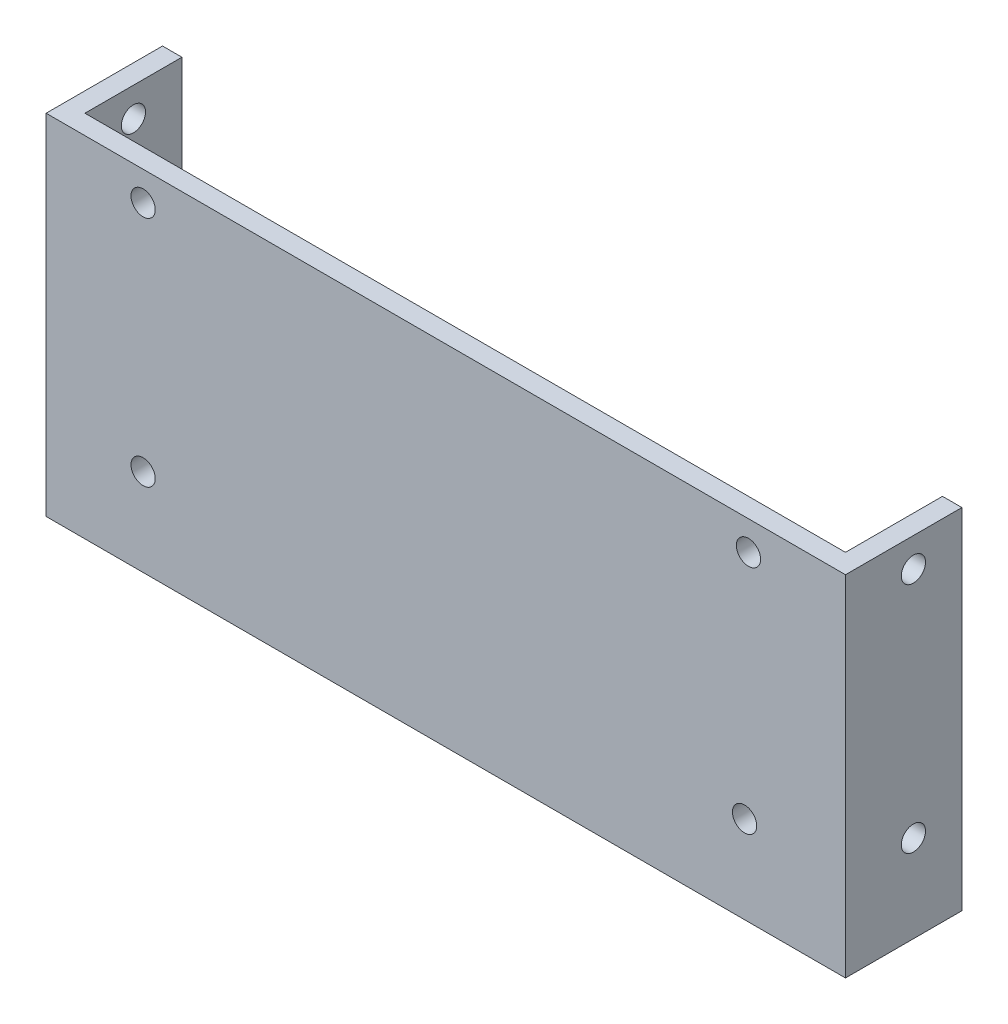
SolidWorks part; units mm, degrees
ref_plane "前视基准面" through (0, 0, 0) normal (0, 0, 1) x (1, 0, 0)
ref_plane "上视基准面" through (0, 0, 0) normal (0, 1, 0) x (1, 0, 0)
ref_plane "右视基准面" through (0, 0, 0) normal (1, 0, 0) x (0, 0, -1)
other "Configuration Table"
sketch "草图1" plane through (0, 0, 0) normal (0, 0, 1) x (1, 0, 0)
  line L1 (0, 0) -> (82.4, 0)
  line L2 (0, 0) -> (0, 6)
  line L3 (0, 6) -> (82.4, 6)
  line L4 (82.4, 0) -> (82.4, 6)
  dimension "D1" = 6
  dimension "D2" = 82.4
extrude "凸台-拉伸1" add sketch "草图1" along normal blind 2
sketch "草图2" plane through (0, 0, 0) normal (0, 0, -1) x (-1, 0, 0)
  line L0 (0, 6) -> (-2, 6)
  line L1 (-82.4, 6) -> (0, 6) construction
  line L2 (-2, 6) -> (-2, 0)
  line L3 (0, 0) -> (-82.4, 0) construction
  line L4 (-2, 0) -> (0, 0)
  line L5 (0, 0) -> (0, 6)
  line L6 (-82.4, 6) -> (-80.4, 6)
  line L7 (-80.4, 6) -> (-80.4, 0)
  line L8 (-80.4, 0) -> (-82.4, 0)
  line L9 (-82.4, 0) -> (-82.4, 6)
  dimension "D1" = 2
  dimension "D2" = 2
extrude "凸台-拉伸2" add sketch "草图2" along normal blind 10
sketch "草图3" plane through (0, 0, 2) normal (0, 0, 1) x (1, 0, 0)
  line L0 (0, 3) -> (82.4, 3) construction
  line L1 (0, 6) -> (0, 0) construction
  line L2 (82.4, 0) -> (82.4, 6) construction
  circle A0 centre (10, 3) radius 1.25
  circle A1 centre (72.4, 3) radius 1.25
  dimension "D1" = 2.5
  dimension "D2" = 2.5
  dimension "D4" = 10
  dimension "D3" = 10
extrude "切除-拉伸1" cut sketch "草图3" against normal up to next
sketch "草图4" plane through (82.4, 0, 0) normal (1, 0, 0) x (0, 0, -1)
  line L0 (-2, 3) -> (10, 3) construction
  line L1 (-2, 0) -> (-2, 6) construction
  line L2 (10, 6) -> (10, 0) construction
  circle A0 centre (5, 3) radius 1.25
  dimension "D1" = 2.5
  dimension "D2" = 7
extrude "切除-拉伸2" cut sketch "草图4" against normal through all both and the other way through all
sketch "草图5" plane through (0, 0, 0) normal (0, -1, 0) x (1, 0, 0)
  line L8 (0, 2) -> (0, -10)
  line L9 (0, -10) -> (2, -10)
  line L10 (2, -10) -> (2, 0)
  line L11 (2, 0) -> (80.4, 0)
  line L12 (80.4, 0) -> (80.4, -10)
  line L13 (80.4, -10) -> (82.4, -10)
  line L14 (82.4, -10) -> (82.4, 2)
  line L15 (82.4, 2) -> (0, 2)
  line L16 (0, 2) -> (0, -10)
  line L17 (0, -10) -> (2, -10)
  line L18 (2, -10) -> (2, 0)
  line L19 (2, 0) -> (80.4, 0)
  line L20 (80.4, 0) -> (80.4, -10)
  line L21 (80.4, -10) -> (82.4, -10)
  line L22 (82.4, -10) -> (82.4, 2)
  line L23 (82.4, 2) -> (0, 2)
  dimension "D1" = 0
extrude "凸台-拉伸3" add sketch "草图5" along normal blind 30
sketch "草图9" plane through (80.4, 0, 0) normal (-1, 0, 0) x (0, 0, 1)
  circle A1 centre (-5, -21) radius 1.25
  dimension "D1" = 2.5
extrude "切除-拉伸3" cut sketch "草图9" against normal through all both and the other way through all
sketch "草图10" plane through (0, 0, 0) normal (0, 0, -1) x (-1, 0, 0)
  circle A0 centre (-10, -21) radius 1.25
  circle A1 centre (-72, -21) radius 1.25
extrude "切除-拉伸4" cut sketch "草图10" against normal through all
